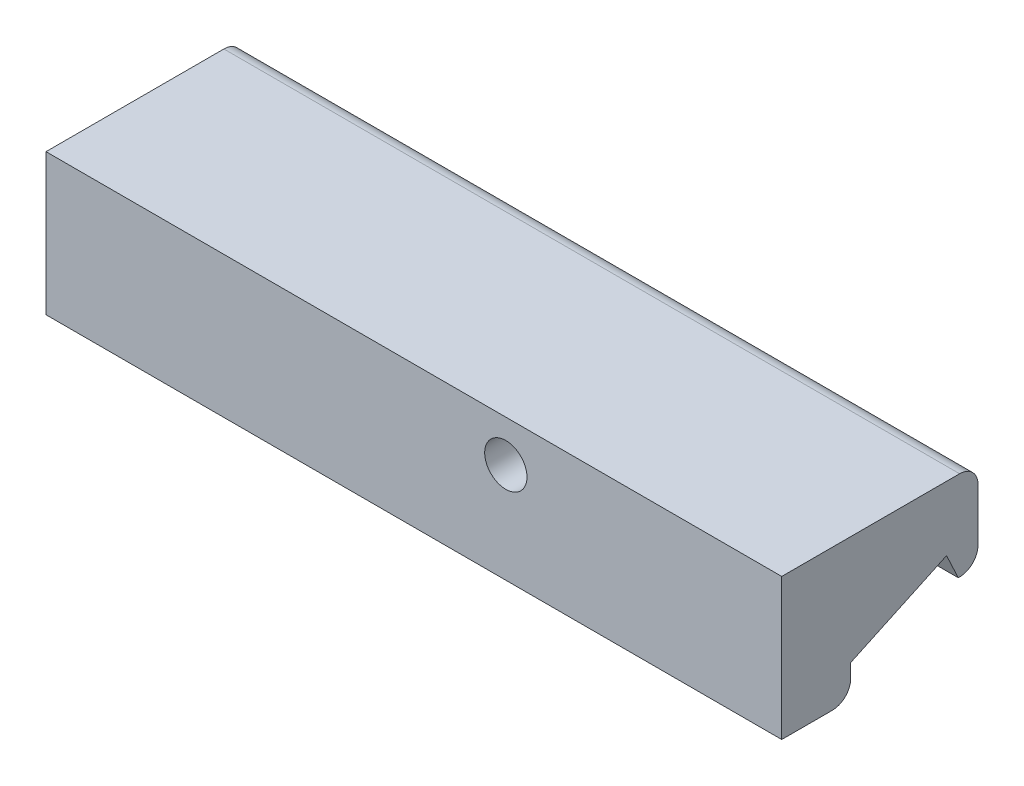
SolidWorks part; units mm, degrees
ref_plane "Front Plane" through (0, 0, 0) normal (0, 0, 1) x (1, 0, 0)
ref_plane "Top Plane" through (0, 0, 0) normal (0, 1, 0) x (1, 0, 0)
ref_plane "Right Plane" through (0, 0, 0) normal (1, 0, 0) x (0, 0, -1)
sketch "Sketch1" plane through (0, 0, 0) normal (1, 0, 0) x (0, 0, -1)
  line L0 (0, 0) -> (5.4995, 0)
  line L2 (21.3407, 7.6355) -> (21.3407, 13.3601)
  line L3 (19.3407, 15.3601) -> (0, 15.3601)
  line L4 (0, 15.3601) -> (0, 0)
  line L6 (19.1904, 5.6412) -> (17.9225, 8.3601)
  line L7 (17.9225, 8.3601) -> (7.5, 3.5)
  line L8 (7.5, 3.5) -> (7.5, 2.0005)
  arc A0 (19.3407, 15.3601) -> (21.3407, 13.3601) centre (19.3407, 13.3601) cw
  arc A1 (19.1904, 5.6412) -> (21.3407, 7.6355) centre (19.3407, 7.6355) ccw
  arc A2 (5.4995, 0) -> (7.5, 2.0005) centre (5.4995, 2.0005) ccw
  dimension "D7" = 4
  dimension "D4" = 4
  dimension "D8" = 4.0011
  dimension "D3" = 11.5
  dimension "D1" = 7.5
  dimension "D5" = 7
  dimension "D6" = 3
extrude "ProfileBoss-Extrude1" add sketch "Sketch1" along normal blind 80
sketch "Sketch2" plane through (0, 0.0022, 0.001) normal (0, -0.9063, -0.4226) x (1, 0, 0)
  line L2 (80, -8.2765) -> (0, -8.2765) construction
  line L3 (0, -8.2765) -> (0, -19.7765) construction
  circle A0 centre (36.15, -14.0265) radius 2.3
  dimension "D1" = 4.6
  dimension "D2" = 5.75
  dimension "D3" = 36.15
extrude "LedStripMountHolesCut-Extrude1" cut sketch "Sketch2" against normal blind 4.5
sketch "Sketch4" plane through (0, 0.0022, 0.001) normal (0, -0.9063, -0.4226) x (1, 0, 0)
  line L5 (80, -19.7765) -> (0, -19.7765) construction
  line L6 (0, -8.2765) -> (28, -8.2765)
  line L7 (0, -8.2765) -> (0, -19.7765)
  line L8 (0, -19.7765) -> (28, -19.7765)
  line L9 (28, -8.2765) -> (28, -19.7765)
  dimension "D2" = 28
extrude "PowerConnectorCut-Extrude4" cut sketch "Sketch4" against normal blind 6.5
sketch "Sketch3" plane through (0, 0, 0) normal (0, 0, 1) x (1, 0, 0)
  line L0 (0, 15.3601) -> (0, 0) construction
  circle A0 centre (50, 10.8601) radius 2.3
  dimension "D1" = 4.6
  dimension "D4" = 4.5
  dimension "D2" = 50
extrude "MountingHolesCut-Extrude3" cut sketch "Sketch3" against normal blind 4.5
equation "\"LightStripShortLength\"= 80mm"
equation "\"D1@ProfileBoss-Extrude1\"=\"LightStripShortLength\""
equation "\"LightStripWidth\"= 11.5mm'Spec"
equation "\"D3@Sketch1\"=\"LightStripWidth\""
equation "\"D2@Sketch2\"=\"LightStripWidth\"/2"
equation "\"LightStripMountHoleFromLeftOrRightEdge\"= ( \"LightStripLength\" - \"LightStripDistanceBetweenMountingHoles\" ) / 2"
equation "\"D3@Sketch2\"=\"LightStripMountHoleFromLeftOrRightEdge\""
equation "\"LightStripGuideMountingHoleFromLeftOrRightSide\"= 50mm"
equation "\"D2@Sketch3\"=\"LightStripGuideMountingHoleFromLeftOrRightSide\""
equation "\"LightStripGuideMountingHoleFromTop\"= 4.5mm"
equation "\"LightStripLength\"= 270mm'From Step file"
equation "\"LightStripDistanceBetweenMountingHoles\"= 197.7mm'From Step file"
